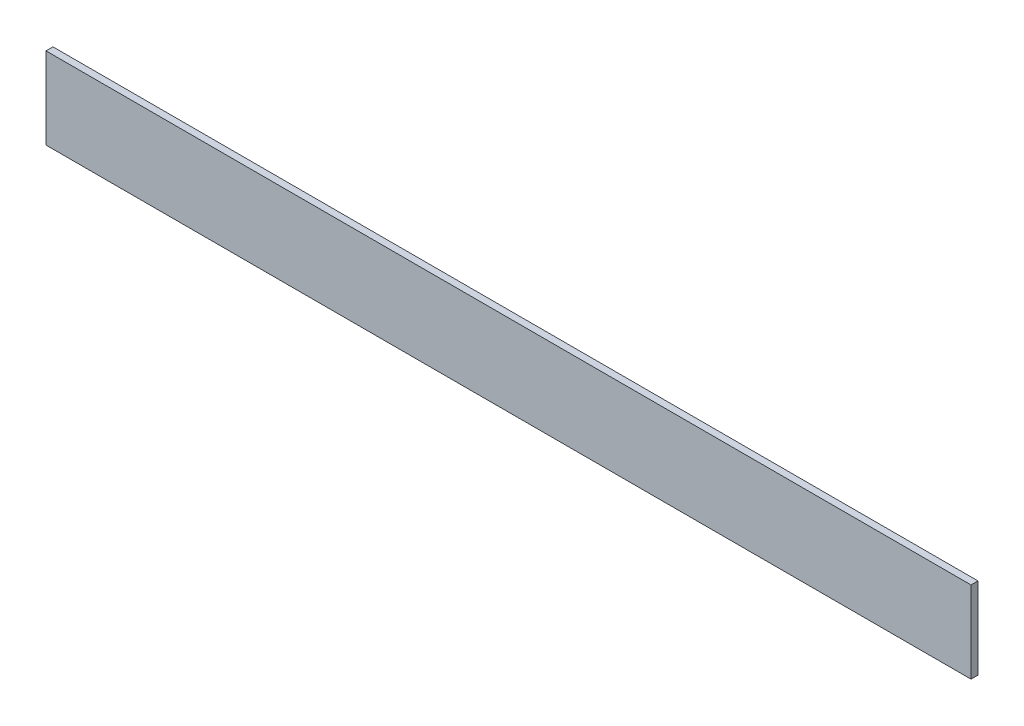
SolidWorks part; units mm, degrees
ref_plane "Front Plane" through (0, 0, 0) normal (0, 0, 1) x (1, 0, 0)
ref_plane "Top Plane" through (0, 0, 0) normal (0, 1, 0) x (1, 0, 0)
ref_plane "Right Plane" through (0, 0, 0) normal (1, 0, 0) x (0, 0, -1)
sketch "Sketch1" plane through (0, 0, 0) normal (1, 0, 0) x (0, 0, -1)
  line L0 (-7.8994, -7.8994) -> (9.525, -7.8994)
  line L1 (-9.525, -9.525) -> (9.525, -9.525)
  line L2 (-9.525, -9.525) -> (-9.525, 9.525)
  line L3 (-7.8994, -7.8994) -> (-7.8994, 9.525)
  line L4 (9.525, -9.525) -> (9.525, -7.8994)
  line L5 (-9.525, 9.525) -> (-7.8994, 9.525)
  dimension "D1" = 19.05
  dimension "D2" = 1.6256
extrude "Boss-Extrude1" add sketch "Sketch1" along normal blind 215.9
sketch "Sketch2" plane through (0, -7.8994, 0) normal (0, 1, 0) x (1, 0, 0)
  line L0 (215.9, -7.8994) -> (0, -7.8994) construction
  line L1 (0, 9.525) -> (19.05, 9.525)
  line L2 (0, 9.525) -> (0, -7.8994)
  line L3 (0, -7.8994) -> (19.05, -7.8994)
  line L4 (19.05, 9.525) -> (19.05, -7.8994)
  line L5 (0, 9.525) -> (19.05, -7.8994) construction
  line L6 (0, -7.8994) -> (19.05, 9.525) construction
  line L8 (215.9, 9.525) -> (196.85, 9.525)
  line L9 (215.9, 9.525) -> (215.9, -7.8994)
  line L10 (215.9, -7.8994) -> (196.85, -7.8994)
  line L11 (196.85, 9.525) -> (196.85, -7.8994)
  line L12 (215.9, 9.525) -> (196.85, -7.8994) construction
  line L13 (215.9, -7.8994) -> (196.85, 9.525) construction
  point P4 (9.525, 0.8128)
  point P12 (206.375, 0.8128)
  dimension "D1" = 19.05
  dimension "D2" = 19.05
extrude "Cut-Extrude1" cut sketch "Sketch2" against normal up to next
